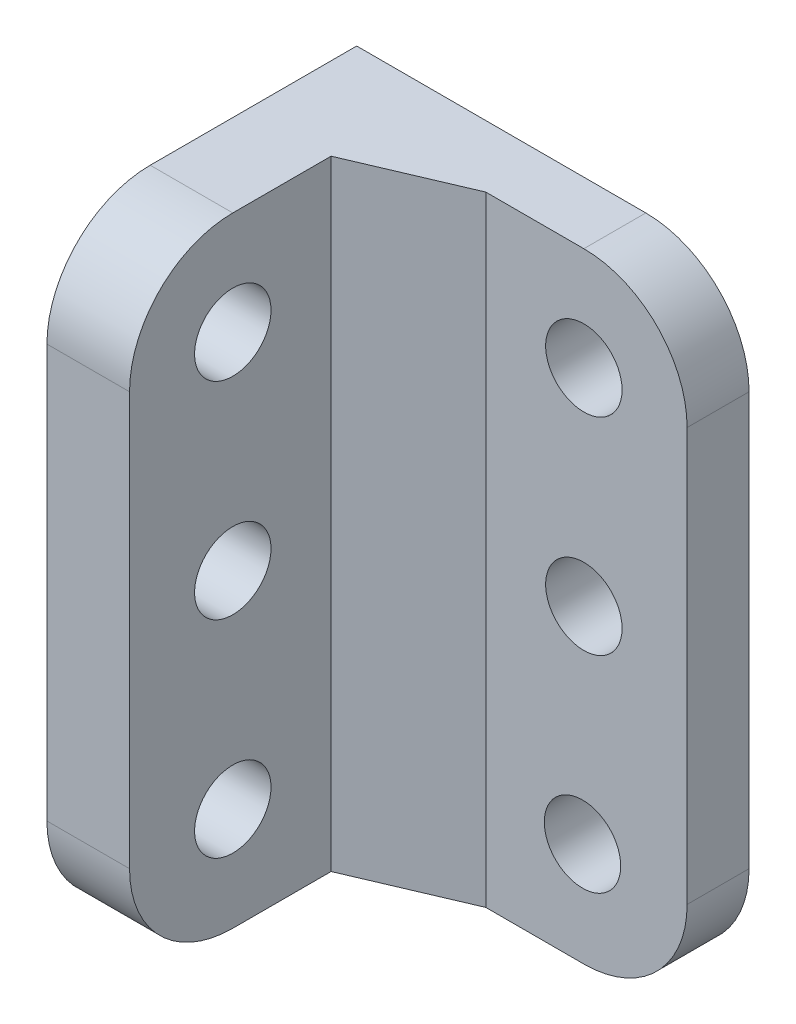
SolidWorks part; units mm, degrees
material "Copper"
ref_plane "Front Plane" through (0, 0, 0) normal (0, 0, 1) x (1, 0, 0)
ref_plane "Top Plane" through (0, 0, 0) normal (0, 1, 0) x (1, 0, 0)
ref_plane "Right Plane" through (0, 0, 0) normal (1, 0, 0) x (0, 0, -1)
sketch "Sketch1" plane through (0, 0, 0) normal (0, 1, 0) x (1, 0, 0)
  line L0 (0, 0) -> (24.13, 0)
  line L1 (24.13, 0) -> (24.13, -3.81)
  line L2 (24.13, -3.81) -> (11.7475, -3.81)
  line L3 (11.7475, -3.81) -> (5.08, -6.6548)
  line L4 (5.08, -6.6548) -> (5.08, -19.05)
  line L5 (5.08, -19.05) -> (0, -19.05)
  line L6 (0, -19.05) -> (0, 0)
  dimension "D1" = 24.13
  dimension "D2" = 19.05
  dimension "D3" = 12.3952
  dimension "D4" = 3.81
  dimension "D5" = 5.08
  dimension "D6" = 12.3825
extrude "Base Extrude" add sketch "Sketch1" along normal blind 38.1
sketch "Sketch2" plane through (0, 0, 3.81) normal (0, 0, 1) x (1, 0, 0)
  line L1 (0, 19.05) -> (24.13, 19.05) construction
  line L2 (0, 38.1) -> (0, 0) construction
  line L3 (24.13, 38.1) -> (24.13, 0) construction
  circle A0 centre (17.6973, 6.35) radius 2.3495
  circle A1 centre (17.78, 19.05) radius 2.3495
  circle A2 centre (17.78, 31.75) radius 2.3495
  point P6 (0, 0)
  dimension "D4" = 4.699
  dimension "D1" = 12.7
  dimension "D2" = 12.7
  dimension "D3" = 6.35
extrude "Motor Hole Cut" cut sketch "Sketch2" against normal through all
sketch "Sketch3" plane through (5.08, 0, 0) normal (1, 0, 0) x (0, 0, -1)
  line L0 (-19.05, 19.05) -> (0, 19.05) construction
  line L1 (-19.05, 38.1) -> (-19.05, 0) construction
  line L2 (0, 38.1) -> (0, 0) construction
  circle A0 centre (-12.7, 31.75) radius 2.3495
  circle A1 centre (-12.7, 19.05) radius 2.3495
  circle A2 centre (-12.7, 6.35) radius 2.3495
  point P12 (0, 0)
  point P13 (0, 0)
  dimension "D2" = 4.699
  dimension "D1" = 12.7
  dimension "D3" = 12.7
  dimension "D4" = 12.7
extrude "Mounting Hole Cut" cut sketch "Sketch3" against normal through all
fillet "Corner Fillets" radius 6.35 4 edges at (24.13, 38.1, 1.905) (24.13, 0, 1.905) (2.54, 0, 19.05) (2.54, 38.1, 19.05)
